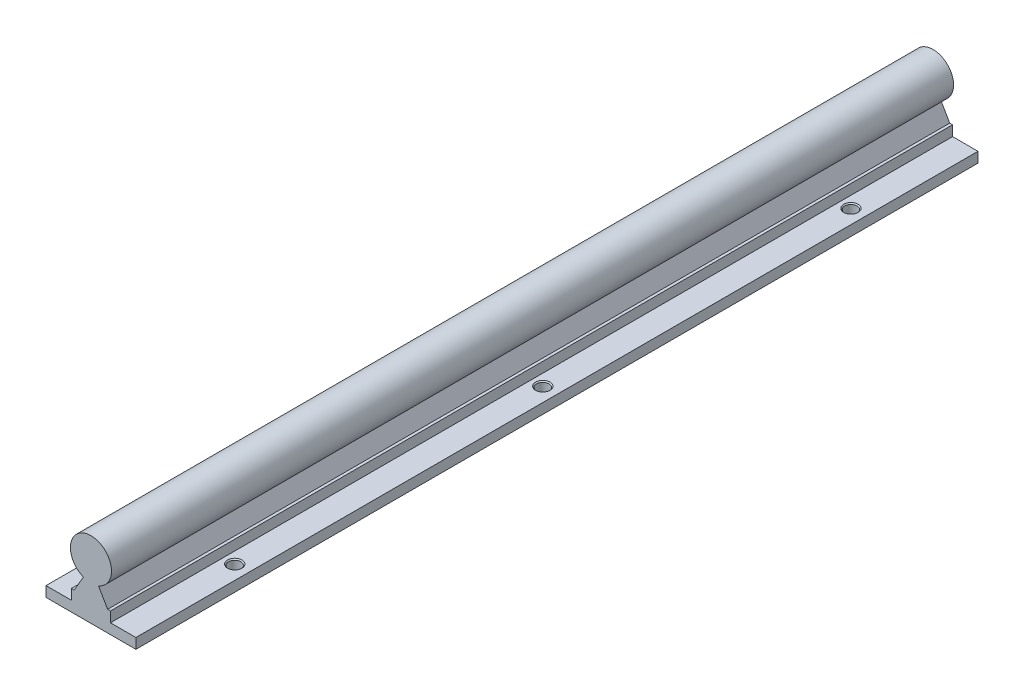
SolidWorks part; units mm, degrees
ref_plane "Alzado" through (0, 0, 0) normal (0, 0, 1) x (1, 0, 0)
ref_plane "Planta" through (0, 0, 0) normal (0, 1, 0) x (1, 0, 0)
ref_plane "Vista lateral" through (0, 0, 0) normal (1, 0, 0) x (0, 0, -1)
sketch "Croquis1" plane through (0, 0, 0) normal (0, 0, 1) x (1, 0, 0)
  line L0 (0, 0) -> (0, 27) construction
  line L1 (-8.1212, 10) -> (-3.6756, 17.7)
  line L2 (-8.1212, 10) -> (-9.5, 10)
  line L3 (-9.5, 10) -> (-9.5, 5)
  line L4 (-9.5, 5) -> (-21.88, 5)
  line L5 (-21.88, 5) -> (-21.88, 0)
  line L6 (-21.88, 0) -> (21.88, 0)
  line L7 (21.88, 5) -> (21.88, 0)
  line L8 (9.5, 5) -> (21.88, 5)
  line L9 (9.5, 10) -> (9.5, 5)
  line L10 (8.1212, 10) -> (9.5, 10)
  line L11 (8.1212, 10) -> (3.6756, 17.7)
  arc A0 (3.6756, 17.7) -> (-3.6756, 17.7) centre (0, 27) ccw
  dimension "D1" = 20
  dimension "D2" = 27
  dimension "D3" = 43.76
  dimension "D4" = 5
  dimension "D5" = 30
  dimension "D6" = 10
  dimension "D7" = 19
  dimension "D8" = 17.7
extrude "Saliente-Extruir1" add sketch "Croquis1" along normal mid plane 410
sketch "Croquis2" plane through (0, 0, 0) normal (0, -1, 0) x (1, 0, 0)
  line L0 (0, 218.8513) -> (0, -218.8513) construction
  line L1 (-21.88, 205) -> (21.88, 205) construction
  circle A0 centre (15, 150) radius 3
  circle A1 centre (-15, 150) radius 3
  circle A2 centre (-15, 0) radius 3
  circle A3 centre (15, 0) radius 3
  circle A6 centre (15, -150) radius 3
  circle A7 centre (-15, -150) radius 3
  point P4 (0, 0)
  dimension "D1" = 6
  dimension "D2" = 55
  dimension "D3" = 150
  dimension "D4" = 30
  dimension "D5" = 30
  dimension "D6" = 150
extrude "Cortar-Extruir1" cut sketch "Croquis2" against normal up to next
chamfer "Chaflán1" distance 0.5 angle 45 6 edges at (-12, 5, 150) (-12, 5, 0) (-12, 5, -150) (18, 5, -150) (18, 5, 0) (18, 5, 150)
